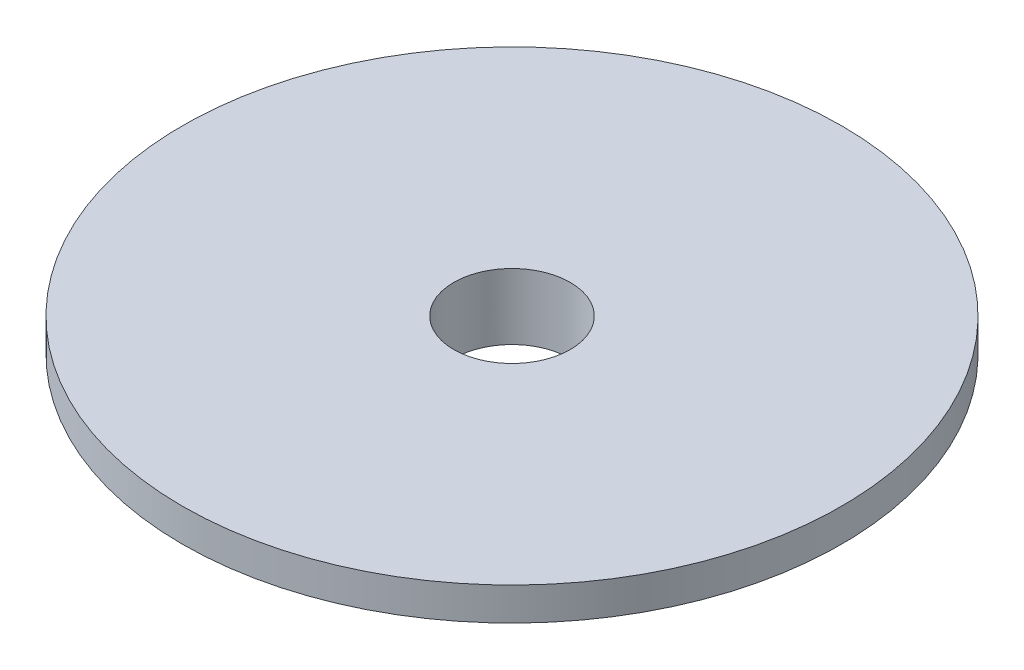
SolidWorks part; units mm, degrees
ref_plane "前视基准面" through (0, 0, 0) normal (0, 0, 1) x (1, 0, 0)
ref_plane "上视基准面" through (0, 0, 0) normal (0, 1, 0) x (1, 0, 0)
ref_plane "右视基准面" through (0, 0, 0) normal (1, 0, 0) x (0, 0, -1)
sketch "草图1" plane through (0, 0, 0) normal (0, 1, 0) x (1, 0, 0)
  circle A0 centre (0, 0) radius 15
  circle A1 centre (0, 0) radius 2.65
  dimension "D1" = 30
  dimension "D2" = 5.3
extrude "凸台-拉伸1" add sketch "草图1" along normal blind 1.5
sketch "草图2" plane through (0, 0, 0) normal (0, -1, 0) x (1, 0, 0)
  circle A0 centre (0, 0) radius 6
  circle A1 centre (0, 0) radius 2.65 construction
  circle A2 centre (0, 0) radius 2.65
  dimension "D1" = 12
extrude "凸台-拉伸3" add sketch "草图2" along normal blind 1.5
